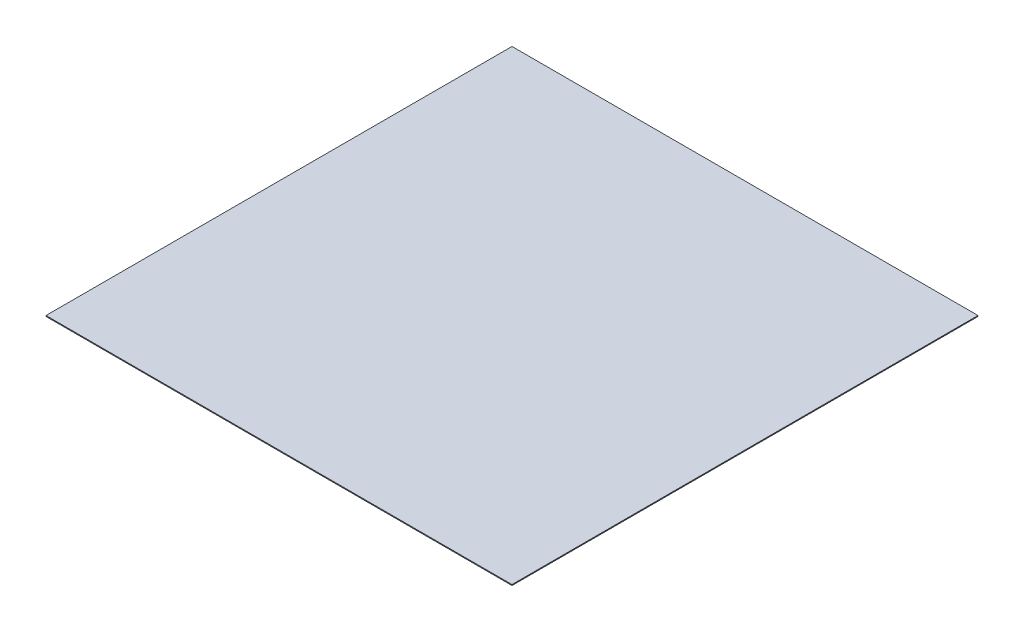
SolidWorks part; units mm, degrees
material "6061-T6 (SS)"
ref_plane "Front Plane" through (0, 0, 0) normal (0, 0, 1) x (1, 0, 0)
ref_plane "Top Plane" through (0, 0, 0) normal (0, 1, 0) x (1, 0, 0)
ref_plane "Right Plane" through (0, 0, 0) normal (1, 0, 0) x (0, 0, -1)
sketch "Sketch1" plane through (0, 0, 0) normal (0, 1, 0) x (1, 0, 0)
  line L1 (1675, -1675) -> (-1675, -1675)
  line L2 (1675, -1675) -> (1675, 1675)
  line L3 (1675, 1675) -> (-1675, 1675)
  line L4 (-1675, -1675) -> (-1675, 1675)
  line L5 (1675, -1675) -> (-1675, 1675) construction
  line L6 (1675, 1675) -> (-1675, -1675) construction
  point P0 (0, 0)
  dimension "D1" = 3350
  dimension "D2" = 3350
extrude "Boss-Extrude1" add sketch "Sketch1" along normal blind 6.35
